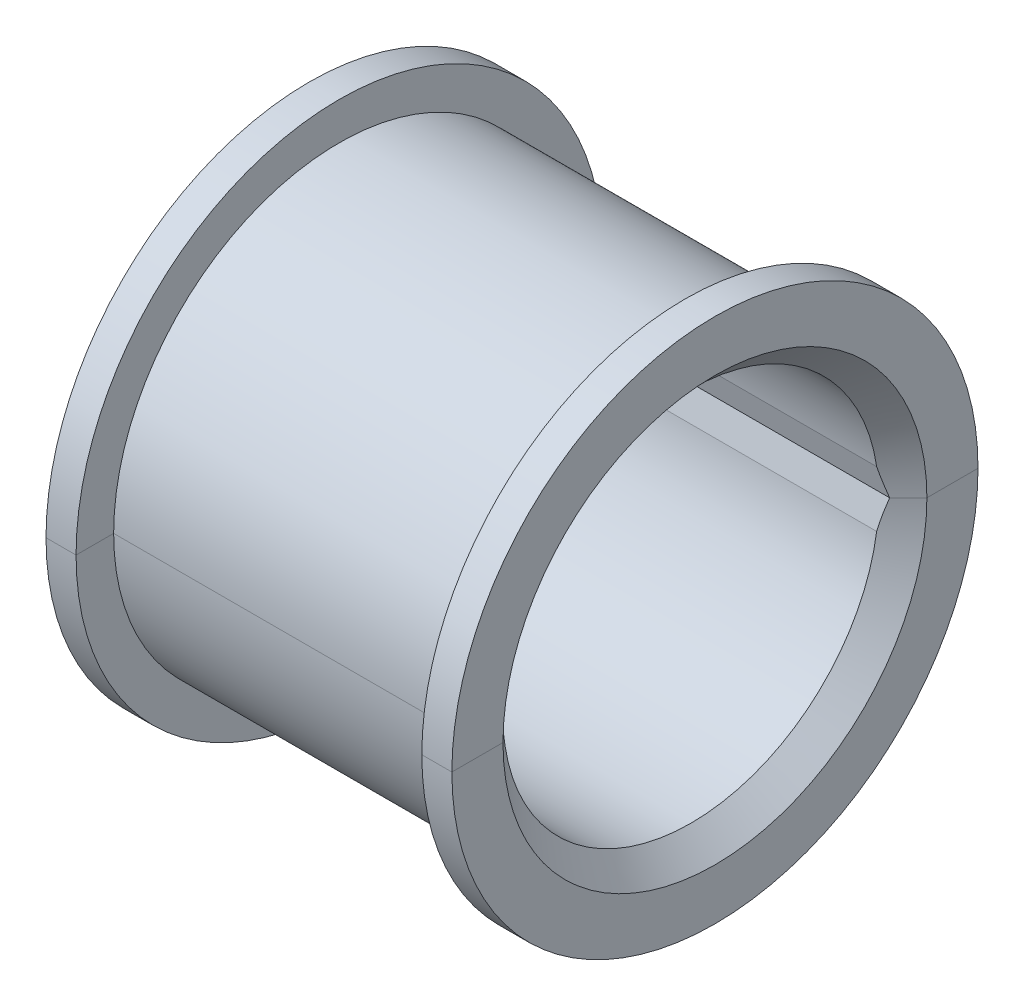
SolidWorks part; units mm, degrees
material "Алюминиевая бронза"
ref_plane "Спереди" through (0, 0, 0) normal (0, 0, 1) x (1, 0, 0)
ref_plane "Сверху" through (0, 0, 0) normal (0, 1, 0) x (1, 0, 0)
ref_plane "Справа" through (0, 0, 0) normal (1, 0, 0) x (0, 0, -1)
sketch "Эскиз1" plane through (0, 0, 0) normal (0, 0, 1) x (1, 0, 0)
  line L0 (-27.196, 0) -> (51.6886, 0) construction
  line L1 (0, 14.1) -> (0, 17.5)
  line L2 (0, 17.5) -> (2, 17.5)
  line L3 (2, 17.5) -> (2, 15)
  line L4 (2, 15) -> (25, 15)
  line L5 (25, 15) -> (25, 17.5)
  line L6 (25, 17.5) -> (27, 17.5)
  line L7 (27, 17.5) -> (27, 14.1)
  line L8 (25.4, 12.5) -> (1.6, 12.5)
  line L9 (1.6, 12.5) -> (0, 14.1)
  line L10 (27, 14.1) -> (25.4, 12.5)
  point P3 (0, 12.5)
  point P11 (27, 12.5)
  dimension "D1" = 25
  dimension "D2" = 30
  dimension "D3" = 35
  dimension "D4" = 23
  dimension "D5" = 2
  dimension "D6" = 27
  dimension "D7" = 1.6
  dimension "D8" = 45
  dimension "D9" = 1.6
  dimension "D10" = 45
revolve "Повернуть1" add sketch "Эскиз1" angle 180 mid plane about L0
sketch "Эскиз2" plane through (0, 0, 0) normal (-1, 0, 0) x (0, 0, 1)
  line L0 (-19.8055, 0) -> (20.1791, 0) construction
  line L1 (0, -19.8755) -> (0, 19.2216) construction
  line L2 (12.8599, 0) -> (12.3599, 1.866)
  line L3 (12.3599, 1.866) -> (12.3599, 0)
  line L4 (12.3599, 0) -> (12.8599, 0)
  line L5 (-12.8599, 0) -> (-12.3599, 1.866)
  line L6 (-12.3599, 1.866) -> (-12.3599, 0)
  line L7 (-12.3599, 0) -> (-12.8599, 0)
  arc A1 (12.5, 0) -> (-12.5, 0) centre (0, 0) ccw construction
  dimension "D1" = 75
  dimension "D2" = 0.5
extrude "Вырез-Вытянуть1" cut sketch "Эскиз2" against normal through all
mirror "Зеркальное отражение1" about plane through (0, 0, 0) normal (0, 1, 0) of bodies 108
